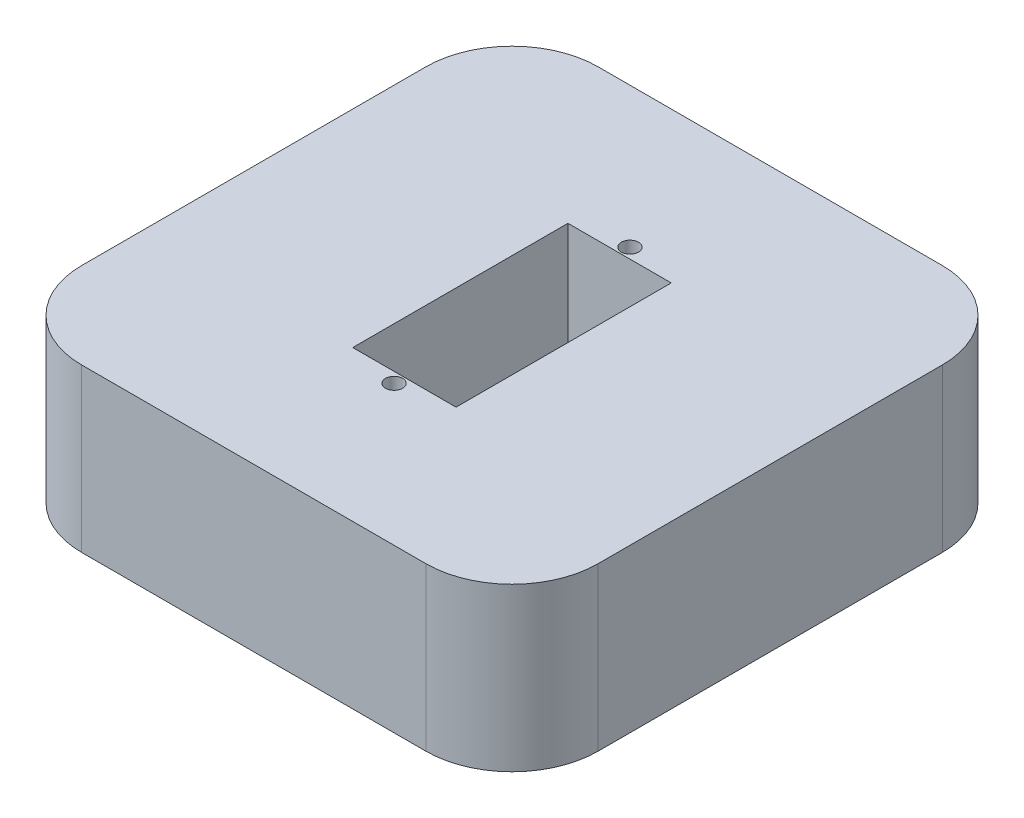
SolidWorks part; units mm, degrees
ref_plane "Front Plane" through (0, 0, 0) normal (0, 0, 1) x (1, 0, 0)
ref_plane "Top Plane" through (0, 0, 0) normal (0, 1, 0) x (1, 0, 0)
ref_plane "Right Plane" through (0, 0, 0) normal (1, 0, 0) x (0, 0, -1)
sketch "Sketch1" plane through (0, 0, 0) normal (0, 1, 0) x (1, 0, 0)
  line L1 (-30, -30) -> (30, -30)
  line L2 (-30, -30) -> (-30, 30)
  line L3 (-30, 30) -> (30, 30)
  line L4 (30, -30) -> (30, 30)
  line L5 (-30, -30) -> (30, 30) construction
  line L6 (-30, 30) -> (30, -30) construction
  point P0 (0, 0)
  point P6 (-34.5816, 26.5514)
extrude "Boss-Extrude1" add sketch "Sketch1" along normal blind 18.87 contours L3 L4 L1 L2
fillet "Fillet1" radius 10 4 edges at (-30, 9.435, -30) (30, 9.435, -30) (30, 9.435, 30) (-30, 9.435, 30)
sketch "Sketch3" plane through (0, 0, 0) normal (0, -1, 0) x (-1, 0, 0)
  line L1 (-6, -12.5) -> (6, -12.5)
  line L2 (-6, -12.5) -> (-6, 12.5)
  line L3 (-6, 12.5) -> (6, 12.5)
  line L4 (6, -12.5) -> (6, 12.5)
  line L5 (-6, -12.5) -> (6, 12.5) construction
  line L6 (-6, 12.5) -> (6, -12.5) construction
  point P0 (0, 0)
extrude "Cut-Extrude1" cut sketch "Sketch3" against normal through all contours L3 L4 L1 L2
sketch "Sketch5" plane through (0, 18.87, 0) normal (0, 1, 0) x (1, 0, 0)
  circle A0 centre (0, 13.7) radius 1
  point P0 (0, 14.0799)
extrude "Cut-Extrude2" cut sketch "Sketch5" against normal through all contours A0
sketch "Sketch8" plane through (0, 18.87, 0) normal (0, 1, 0) x (1, 0, 0)
  circle A0 centre (0, -13.7) radius 1
  point P0 (0, -12.5)
extrude "Cut-Extrude3" cut sketch "Sketch8" against normal through all contours A0
